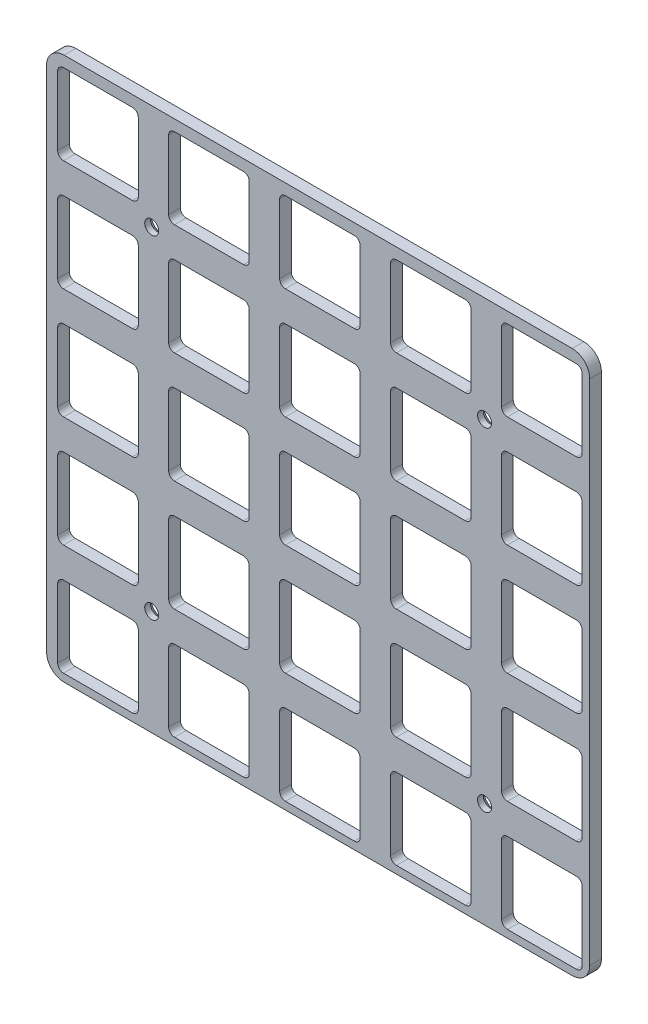
SolidWorks part; units mm, degrees
ref_plane "Front Plane" through (0, 0, 0) normal (0, 0, 1) x (1, 0, 0)
ref_plane "Top Plane" through (0, 0, 0) normal (0, 1, 0) x (1, 0, 0)
ref_plane "Right Plane" through (0, 0, 0) normal (1, 0, 0) x (0, 0, -1)
sketch "Sketch2" plane through (0, 0, 0) normal (0, 0, 1) x (1, 0, 0)
  line L0 (-43.5, 46.5) -> (43.5, 46.5)
  line L1 (-43.5, -47.5) -> (43.5, -47.5) construction
  line L2 (-47.5, -43.5) -> (-47.5, 43.5) construction
  line L3 (-43.5, 47.5) -> (43.5, 47.5) construction
  line L4 (47.5, -43.5) -> (47.5, 43.5) construction
  line L5 (-43.5, -43.5) -> (43.5, 43.5) construction
  line L6 (-43.5, 43.5) -> (43.5, -43.5) construction
  line L7 (46.5, -43.5) -> (46.5, 43.5)
  line L8 (-43.5, -46.5) -> (43.5, -46.5)
  line L9 (-46.5, -43.5) -> (-46.5, 43.5)
  line L10 (-25.6, 43.6) -> (-25.6, 31.8)
  line L11 (-43.6, 44.6) -> (-31.8, 44.6)
  line L12 (-44.6, 43.6) -> (-44.6, 31.8)
  line L13 (-43.6, 30.8) -> (-31.8, 30.8)
  line L14 (-30.8, 43.6) -> (-30.8, 31.8)
  line L15 (-24.6, 44.6) -> (-12.8, 44.6)
  line L16 (-11.8, 43.6) -> (-11.8, 31.8)
  line L17 (-24.6, 30.8) -> (-12.8, 30.8)
  line L18 (-6.6, 43.6) -> (-6.6, 31.8)
  line L19 (-5.6, 44.6) -> (6.2, 44.6)
  line L20 (7.2, 43.6) -> (7.2, 31.8)
  line L21 (-5.6, 30.8) -> (6.2, 30.8)
  line L22 (12.4, 43.6) -> (12.4, 31.8)
  line L23 (13.4, 44.6) -> (25.2, 44.6)
  line L24 (26.2, 43.6) -> (26.2, 31.8)
  line L25 (13.4, 30.8) -> (25.2, 30.8)
  line L26 (31.4, 43.6) -> (31.4, 31.8)
  line L27 (32.4, 44.6) -> (44.2, 44.6)
  line L28 (45.2, 43.6) -> (45.2, 31.8)
  line L29 (32.4, 30.8) -> (44.2, 30.8)
  line L30 (-25.6, 24.6) -> (-25.6, 12.8)
  line L31 (-24.6, 25.6) -> (-12.8, 25.6)
  line L32 (-11.8, 24.6) -> (-11.8, 12.8)
  line L33 (-24.6, 11.8) -> (-12.8, 11.8)
  line L34 (-6.6, 24.6) -> (-6.6, 12.8)
  line L35 (-5.6, 25.6) -> (6.2, 25.6)
  line L36 (7.2, 24.6) -> (7.2, 12.8)
  line L37 (-5.6, 11.8) -> (6.2, 11.8)
  line L38 (12.4, 24.6) -> (12.4, 12.8)
  line L39 (13.4, 25.6) -> (25.2, 25.6)
  line L40 (26.2, 24.6) -> (26.2, 12.8)
  line L41 (13.4, 11.8) -> (25.2, 11.8)
  line L42 (31.4, 24.6) -> (31.4, 12.8)
  line L43 (32.4, 25.6) -> (44.2, 25.6)
  line L44 (45.2, 24.6) -> (45.2, 12.8)
  line L45 (32.4, 11.8) -> (44.2, 11.8)
  line L46 (-25.6, 5.6) -> (-25.6, -6.2)
  line L47 (-24.6, 6.6) -> (-12.8, 6.6)
  line L48 (-11.8, 5.6) -> (-11.8, -6.2)
  line L49 (-24.6, -7.2) -> (-12.8, -7.2)
  line L50 (-6.6, 5.6) -> (-6.6, -6.2)
  line L51 (-5.6, 6.6) -> (6.2, 6.6)
  line L52 (7.2, 5.6) -> (7.2, -6.2)
  line L53 (-5.6, -7.2) -> (6.2, -7.2)
  line L54 (12.4, 5.6) -> (12.4, -6.2)
  line L55 (13.4, 6.6) -> (25.2, 6.6)
  line L56 (26.2, 5.6) -> (26.2, -6.2)
  line L57 (13.4, -7.2) -> (25.2, -7.2)
  line L58 (31.4, 5.6) -> (31.4, -6.2)
  line L59 (32.4, 6.6) -> (44.2, 6.6)
  line L60 (45.2, 5.6) -> (45.2, -6.2)
  line L61 (32.4, -7.2) -> (44.2, -7.2)
  line L62 (-25.6, -13.4) -> (-25.6, -25.2)
  line L63 (-24.6, -12.4) -> (-12.8, -12.4)
  line L64 (-11.8, -13.4) -> (-11.8, -25.2)
  line L65 (-24.6, -26.2) -> (-12.8, -26.2)
  line L66 (-6.6, -13.4) -> (-6.6, -25.2)
  line L67 (-5.6, -12.4) -> (6.2, -12.4)
  line L68 (7.2, -13.4) -> (7.2, -25.2)
  line L69 (-5.6, -26.2) -> (6.2, -26.2)
  line L70 (12.4, -13.4) -> (12.4, -25.2)
  line L71 (13.4, -12.4) -> (25.2, -12.4)
  line L72 (26.2, -13.4) -> (26.2, -25.2)
  line L73 (13.4, -26.2) -> (25.2, -26.2)
  line L74 (31.4, -13.4) -> (31.4, -25.2)
  line L75 (32.4, -12.4) -> (44.2, -12.4)
  line L76 (45.2, -13.4) -> (45.2, -25.2)
  line L77 (32.4, -26.2) -> (44.2, -26.2)
  line L78 (-25.6, -32.4) -> (-25.6, -44.2)
  line L79 (-24.6, -31.4) -> (-12.8, -31.4)
  line L80 (-11.8, -32.4) -> (-11.8, -44.2)
  line L81 (-24.6, -45.2) -> (-12.8, -45.2)
  line L82 (-6.6, -32.4) -> (-6.6, -44.2)
  line L83 (-5.6, -31.4) -> (6.2, -31.4)
  line L84 (7.2, -32.4) -> (7.2, -44.2)
  line L85 (-5.6, -45.2) -> (6.2, -45.2)
  line L86 (12.4, -32.4) -> (12.4, -44.2)
  line L87 (13.4, -31.4) -> (25.2, -31.4)
  line L88 (26.2, -32.4) -> (26.2, -44.2)
  line L89 (13.4, -45.2) -> (25.2, -45.2)
  line L90 (31.4, -32.4) -> (31.4, -44.2)
  line L91 (32.4, -31.4) -> (44.2, -31.4)
  line L92 (45.2, -32.4) -> (45.2, -44.2)
  line L93 (32.4, -45.2) -> (44.2, -45.2)
  line L94 (-44.6, 24.6) -> (-44.6, 12.8)
  line L95 (-43.6, 25.6) -> (-31.8, 25.6)
  line L96 (-30.8, 24.6) -> (-30.8, 12.8)
  line L97 (-43.6, 11.8) -> (-31.8, 11.8)
  line L98 (-44.6, 5.6) -> (-44.6, -6.2)
  line L99 (-43.6, 6.6) -> (-31.8, 6.6)
  line L100 (-30.8, 5.6) -> (-30.8, -6.2)
  line L101 (-43.6, -7.2) -> (-31.8, -7.2)
  line L102 (-44.6, -13.4) -> (-44.6, -25.2)
  line L103 (-43.6, -12.4) -> (-31.8, -12.4)
  line L104 (-30.8, -13.4) -> (-30.8, -25.2)
  line L105 (-43.6, -26.2) -> (-31.8, -26.2)
  line L106 (-44.6, -32.4) -> (-44.6, -44.2)
  line L107 (-43.6, -31.4) -> (-31.8, -31.4)
  line L108 (-30.8, -32.4) -> (-30.8, -44.2)
  line L109 (-43.6, -45.2) -> (-31.8, -45.2)
  line L110 (-44.6, 43.6) -> (-25.6, 43.6) construction
  line L111 (-44.6, 43.6) -> (-44.6, 24.6) construction
  arc A0 (-43.5, -47.5) -> (-47.5, -43.5) centre (-43.5, -43.5) cw construction
  arc A1 (43.5, -47.5) -> (47.5, -43.5) centre (43.5, -43.5) ccw construction
  arc A2 (43.5, 47.5) -> (47.5, 43.5) centre (43.5, 43.5) cw construction
  arc A3 (-47.5, 43.5) -> (-43.5, 47.5) centre (-43.5, 43.5) cw construction
  arc A4 (43.5, 46.5) -> (46.5, 43.5) centre (43.5, 43.5) cw
  arc A5 (43.5, -46.5) -> (46.5, -43.5) centre (43.5, -43.5) ccw
  arc A6 (-43.5, -46.5) -> (-46.5, -43.5) centre (-43.5, -43.5) cw
  arc A7 (-46.5, 43.5) -> (-43.5, 46.5) centre (-43.5, 43.5) cw
  arc A8 (-44.6, 31.8) -> (-43.6, 30.8) centre (-43.6, 31.8) ccw
  arc A9 (-31.8, 30.8) -> (-30.8, 31.8) centre (-31.8, 31.8) ccw
  arc A10 (-31.8, 44.6) -> (-30.8, 43.6) centre (-31.8, 43.6) cw
  arc A11 (-43.6, 44.6) -> (-44.6, 43.6) centre (-43.6, 43.6) ccw
  arc A12 (-24.6, 44.6) -> (-25.6, 43.6) centre (-24.6, 43.6) ccw
  arc A13 (-25.6, 31.8) -> (-24.6, 30.8) centre (-24.6, 31.8) ccw
  arc A14 (-12.8, 44.6) -> (-11.8, 43.6) centre (-12.8, 43.6) cw
  arc A15 (-12.8, 30.8) -> (-11.8, 31.8) centre (-12.8, 31.8) ccw
  arc A16 (-5.6, 44.6) -> (-6.6, 43.6) centre (-5.6, 43.6) ccw
  arc A17 (-6.6, 31.8) -> (-5.6, 30.8) centre (-5.6, 31.8) ccw
  arc A18 (6.2, 44.6) -> (7.2, 43.6) centre (6.2, 43.6) cw
  arc A19 (6.2, 30.8) -> (7.2, 31.8) centre (6.2, 31.8) ccw
  arc A20 (13.4, 44.6) -> (12.4, 43.6) centre (13.4, 43.6) ccw
  arc A21 (12.4, 31.8) -> (13.4, 30.8) centre (13.4, 31.8) ccw
  arc A22 (25.2, 44.6) -> (26.2, 43.6) centre (25.2, 43.6) cw
  arc A23 (25.2, 30.8) -> (26.2, 31.8) centre (25.2, 31.8) ccw
  arc A24 (32.4, 44.6) -> (31.4, 43.6) centre (32.4, 43.6) ccw
  arc A25 (31.4, 31.8) -> (32.4, 30.8) centre (32.4, 31.8) ccw
  arc A26 (44.2, 44.6) -> (45.2, 43.6) centre (44.2, 43.6) cw
  arc A27 (44.2, 30.8) -> (45.2, 31.8) centre (44.2, 31.8) ccw
  arc A28 (-24.6, 25.6) -> (-25.6, 24.6) centre (-24.6, 24.6) ccw
  arc A29 (-25.6, 12.8) -> (-24.6, 11.8) centre (-24.6, 12.8) ccw
  arc A30 (-12.8, 25.6) -> (-11.8, 24.6) centre (-12.8, 24.6) cw
  arc A31 (-12.8, 11.8) -> (-11.8, 12.8) centre (-12.8, 12.8) ccw
  arc A32 (-5.6, 25.6) -> (-6.6, 24.6) centre (-5.6, 24.6) ccw
  arc A33 (-6.6, 12.8) -> (-5.6, 11.8) centre (-5.6, 12.8) ccw
  arc A34 (6.2, 25.6) -> (7.2, 24.6) centre (6.2, 24.6) cw
  arc A35 (6.2, 11.8) -> (7.2, 12.8) centre (6.2, 12.8) ccw
  arc A36 (13.4, 25.6) -> (12.4, 24.6) centre (13.4, 24.6) ccw
  arc A37 (12.4, 12.8) -> (13.4, 11.8) centre (13.4, 12.8) ccw
  arc A38 (25.2, 25.6) -> (26.2, 24.6) centre (25.2, 24.6) cw
  arc A39 (25.2, 11.8) -> (26.2, 12.8) centre (25.2, 12.8) ccw
  arc A40 (32.4, 25.6) -> (31.4, 24.6) centre (32.4, 24.6) ccw
  arc A41 (31.4, 12.8) -> (32.4, 11.8) centre (32.4, 12.8) ccw
  arc A42 (44.2, 25.6) -> (45.2, 24.6) centre (44.2, 24.6) cw
  arc A43 (44.2, 11.8) -> (45.2, 12.8) centre (44.2, 12.8) ccw
  arc A44 (-24.6, 6.6) -> (-25.6, 5.6) centre (-24.6, 5.6) ccw
  arc A45 (-25.6, -6.2) -> (-24.6, -7.2) centre (-24.6, -6.2) ccw
  arc A46 (-12.8, 6.6) -> (-11.8, 5.6) centre (-12.8, 5.6) cw
  arc A47 (-12.8, -7.2) -> (-11.8, -6.2) centre (-12.8, -6.2) ccw
  arc A48 (-5.6, 6.6) -> (-6.6, 5.6) centre (-5.6, 5.6) ccw
  arc A49 (-6.6, -6.2) -> (-5.6, -7.2) centre (-5.6, -6.2) ccw
  arc A50 (6.2, 6.6) -> (7.2, 5.6) centre (6.2, 5.6) cw
  arc A51 (6.2, -7.2) -> (7.2, -6.2) centre (6.2, -6.2) ccw
  arc A52 (13.4, 6.6) -> (12.4, 5.6) centre (13.4, 5.6) ccw
  arc A53 (12.4, -6.2) -> (13.4, -7.2) centre (13.4, -6.2) ccw
  arc A54 (25.2, 6.6) -> (26.2, 5.6) centre (25.2, 5.6) cw
  arc A55 (25.2, -7.2) -> (26.2, -6.2) centre (25.2, -6.2) ccw
  arc A56 (32.4, 6.6) -> (31.4, 5.6) centre (32.4, 5.6) ccw
  arc A57 (31.4, -6.2) -> (32.4, -7.2) centre (32.4, -6.2) ccw
  arc A58 (44.2, 6.6) -> (45.2, 5.6) centre (44.2, 5.6) cw
  arc A59 (44.2, -7.2) -> (45.2, -6.2) centre (44.2, -6.2) ccw
  arc A60 (-24.6, -12.4) -> (-25.6, -13.4) centre (-24.6, -13.4) ccw
  arc A61 (-25.6, -25.2) -> (-24.6, -26.2) centre (-24.6, -25.2) ccw
  arc A62 (-12.8, -12.4) -> (-11.8, -13.4) centre (-12.8, -13.4) cw
  arc A63 (-12.8, -26.2) -> (-11.8, -25.2) centre (-12.8, -25.2) ccw
  arc A64 (-5.6, -12.4) -> (-6.6, -13.4) centre (-5.6, -13.4) ccw
  arc A65 (-6.6, -25.2) -> (-5.6, -26.2) centre (-5.6, -25.2) ccw
  arc A66 (6.2, -12.4) -> (7.2, -13.4) centre (6.2, -13.4) cw
  arc A67 (6.2, -26.2) -> (7.2, -25.2) centre (6.2, -25.2) ccw
  arc A68 (13.4, -12.4) -> (12.4, -13.4) centre (13.4, -13.4) ccw
  arc A69 (12.4, -25.2) -> (13.4, -26.2) centre (13.4, -25.2) ccw
  arc A70 (25.2, -12.4) -> (26.2, -13.4) centre (25.2, -13.4) cw
  arc A71 (25.2, -26.2) -> (26.2, -25.2) centre (25.2, -25.2) ccw
  arc A72 (32.4, -12.4) -> (31.4, -13.4) centre (32.4, -13.4) ccw
  arc A73 (31.4, -25.2) -> (32.4, -26.2) centre (32.4, -25.2) ccw
  arc A74 (44.2, -12.4) -> (45.2, -13.4) centre (44.2, -13.4) cw
  arc A75 (44.2, -26.2) -> (45.2, -25.2) centre (44.2, -25.2) ccw
  arc A76 (-24.6, -31.4) -> (-25.6, -32.4) centre (-24.6, -32.4) ccw
  arc A77 (-25.6, -44.2) -> (-24.6, -45.2) centre (-24.6, -44.2) ccw
  arc A78 (-12.8, -31.4) -> (-11.8, -32.4) centre (-12.8, -32.4) cw
  arc A79 (-12.8, -45.2) -> (-11.8, -44.2) centre (-12.8, -44.2) ccw
  arc A80 (-5.6, -31.4) -> (-6.6, -32.4) centre (-5.6, -32.4) ccw
  arc A81 (-6.6, -44.2) -> (-5.6, -45.2) centre (-5.6, -44.2) ccw
  arc A82 (6.2, -31.4) -> (7.2, -32.4) centre (6.2, -32.4) cw
  arc A83 (6.2, -45.2) -> (7.2, -44.2) centre (6.2, -44.2) ccw
  arc A84 (13.4, -31.4) -> (12.4, -32.4) centre (13.4, -32.4) ccw
  arc A85 (12.4, -44.2) -> (13.4, -45.2) centre (13.4, -44.2) ccw
  arc A86 (25.2, -31.4) -> (26.2, -32.4) centre (25.2, -32.4) cw
  arc A87 (25.2, -45.2) -> (26.2, -44.2) centre (25.2, -44.2) ccw
  arc A88 (32.4, -31.4) -> (31.4, -32.4) centre (32.4, -32.4) ccw
  arc A89 (31.4, -44.2) -> (32.4, -45.2) centre (32.4, -44.2) ccw
  arc A90 (44.2, -31.4) -> (45.2, -32.4) centre (44.2, -32.4) cw
  arc A91 (44.2, -45.2) -> (45.2, -44.2) centre (44.2, -44.2) ccw
  arc A92 (-43.6, 25.6) -> (-44.6, 24.6) centre (-43.6, 24.6) ccw
  arc A93 (-44.6, 12.8) -> (-43.6, 11.8) centre (-43.6, 12.8) ccw
  arc A94 (-31.8, 25.6) -> (-30.8, 24.6) centre (-31.8, 24.6) cw
  arc A95 (-31.8, 11.8) -> (-30.8, 12.8) centre (-31.8, 12.8) ccw
  arc A96 (-43.6, 6.6) -> (-44.6, 5.6) centre (-43.6, 5.6) ccw
  arc A97 (-44.6, -6.2) -> (-43.6, -7.2) centre (-43.6, -6.2) ccw
  arc A98 (-31.8, 6.6) -> (-30.8, 5.6) centre (-31.8, 5.6) cw
  arc A99 (-31.8, -7.2) -> (-30.8, -6.2) centre (-31.8, -6.2) ccw
  arc A100 (-43.6, -12.4) -> (-44.6, -13.4) centre (-43.6, -13.4) ccw
  arc A101 (-44.6, -25.2) -> (-43.6, -26.2) centre (-43.6, -25.2) ccw
  arc A102 (-31.8, -12.4) -> (-30.8, -13.4) centre (-31.8, -13.4) cw
  arc A103 (-31.8, -26.2) -> (-30.8, -25.2) centre (-31.8, -25.2) ccw
  arc A104 (-43.6, -31.4) -> (-44.6, -32.4) centre (-43.6, -32.4) ccw
  arc A105 (-44.6, -44.2) -> (-43.6, -45.2) centre (-43.6, -44.2) ccw
  arc A106 (-31.8, -31.4) -> (-30.8, -32.4) centre (-31.8, -32.4) cw
  arc A107 (-31.8, -45.2) -> (-30.8, -44.2) centre (-31.8, -44.2) ccw
  point P0 (0, 0)
  dimension "D1" = 4
  dimension "D4" = 1
  dimension "D2" = 95
  dimension "D5" = 13.8
  dimension "D6" = 2.9
  dimension "D9" = 90
  dimension "D10" = 19
  dimension "D11" = 19
  dimension "D3" = 1
  dimension "D7" = 5
  dimension "D8" = 5
extrude "Boss-Extrude1" add sketch "Sketch2" along normal blind 2
sketch "Sketch3" plane through (0, 0, 0) normal (0, 0, -1) x (-1, 0, 0)
  line L0 (43.5, 43.5) -> (-43.5, -43.5) construction
  line L1 (43.5, 43.5) -> (-43.5, -43.5) construction
  point P2 (-28.5, -28.5)
  point P32 (-28.5, 28.5)
  point P34 (28.5, 28.5)
  point P36 (28.5, -28.5)
  point P38 (0, 0)
  point P39 (0, 0)
  point P40 (0, 0)
  dimension "D1" = 28.5
  dimension "D2" = 57
  dimension "D3" = 4
  dimension "D4" = 40.3051
hole_wizard "CSK for M2 Flat Head Machine Screw5" positions "Sketch3" profile "Sketch7" countersink size "M2" standard "ANSI Metric" end condition through all
sketch "Sketch7" plane through (-28.5, -28.5, 0) normal (1, 0, 0) x (0, 1, 0)
  line L0 (0, 0) -> (0, 2)
  line L1 (0, 2) -> (1.2, 2)
  line L2 (1.2, 2) -> (1.2, 1)
  line L3 (1.2, 1) -> (2.2, 0)
  line L5 (2.2, 0) -> (0, 0)
  line L6 (-1.2, 1) -> (-2.2, 0) construction
  line L11 (0, -6.35) -> (0, 107.95) construction
  dimension "Thru Hole Dia." = 2.4
  dimension "Thru Hole Depth" = 2
  dimension "Near C'Sink Dia." = 4.4
  dimension "Near C'Sink Angle" = 90
